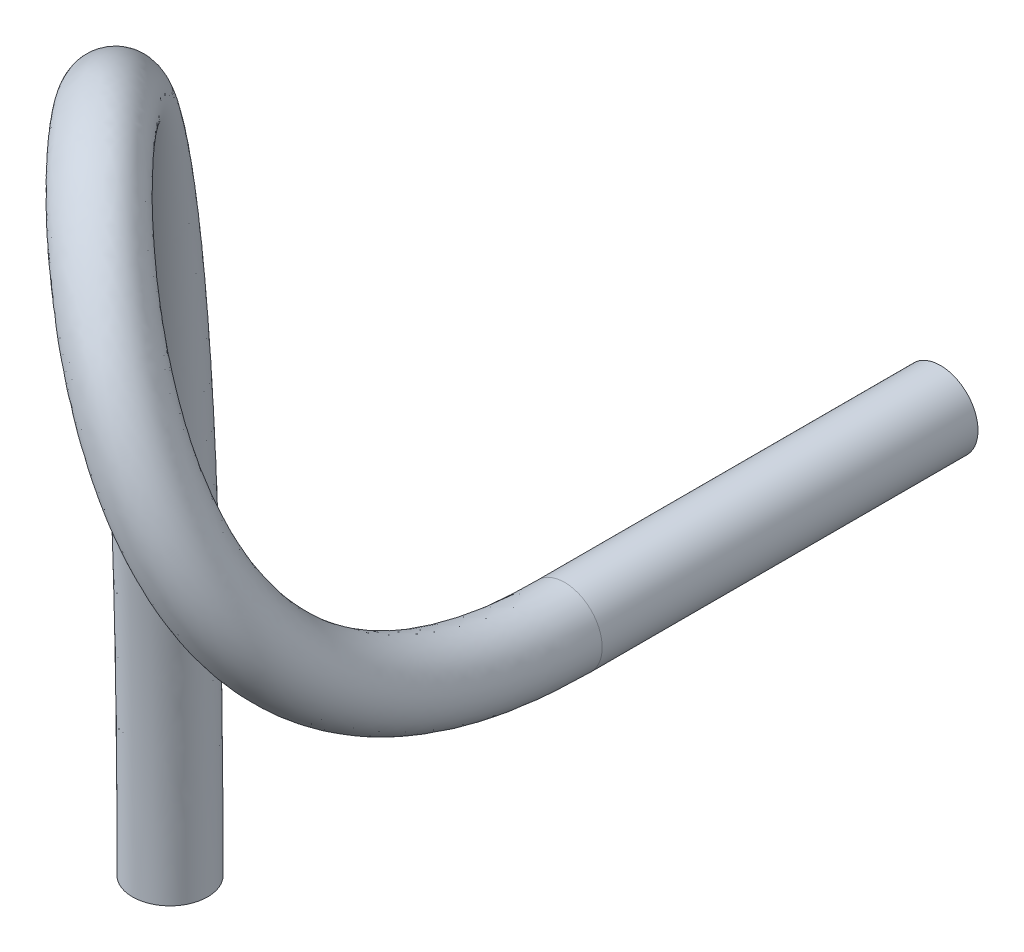
SolidWorks part; units mm, degrees
ref_plane "Front" through (0, 0, 0) normal (0, 0, 1) x (1, 0, 0)
ref_plane "Top" through (0, 0, 0) normal (0, 1, 0) x (1, 0, 0)
ref_plane "Right" through (0, 0, 0) normal (1, 0, 0) x (0, 0, -1)
sketch "Skizze1" plane through (0, 0, 0) normal (0, 1, 0) x (1, 0, 0)
  circle A0 centre (0, 0) radius 0.75
  circle A1 centre (0, 0) radius 1
  dimension "D1" = 2
  dimension "D2" = 1.5
sketch "Skizze2" plane through (0, 0, 0) normal (0, 0, 1) x (1, 0, 0)
  line L0 (0, 0) -> (0, -67038.9479) construction
  line L1 (0, 0) -> (67038.9479, 0) construction
  point P5 (10.5, 11)
  dimension "D1" = 11
  dimension "D2" = 10.5
sketch3d "3D-Skizze1"
  line L0 (0, 0, 0) -> (0, -67038.9479, 0) construction
  line L1 (10.5, 11, 0.0123) -> (10.5, 11, -49999.9877) construction
  spline S0 degree 3 poles (0, 0, 0) (0, 41.6189, 0) (10.5, 11, 18.976) (10.5, 11, 0) knots 0 0 0 0 1 1 1 1
  dimension "D1" = 10
  dimension "D2" = 10
sweep "Austragung1" add profiles "Skizze1" path "3D-Skizze1"
sketch "Skizze3" plane through (0, 0, 0) normal (0, 0, -1) x (-1, 0, 0)
  circle A0 centre (-10.5, 11) radius 0.75 construction
  circle A1 centre (-10.5, 11) radius 1
  circle A2 centre (-10.5, 11) radius 1
  circle A3 centre (-10.5, 11) radius 0.75
  dimension "D1" = 0
extrude "Aufsatz-Linear austragen1" add sketch "Skizze3" along normal blind 10
